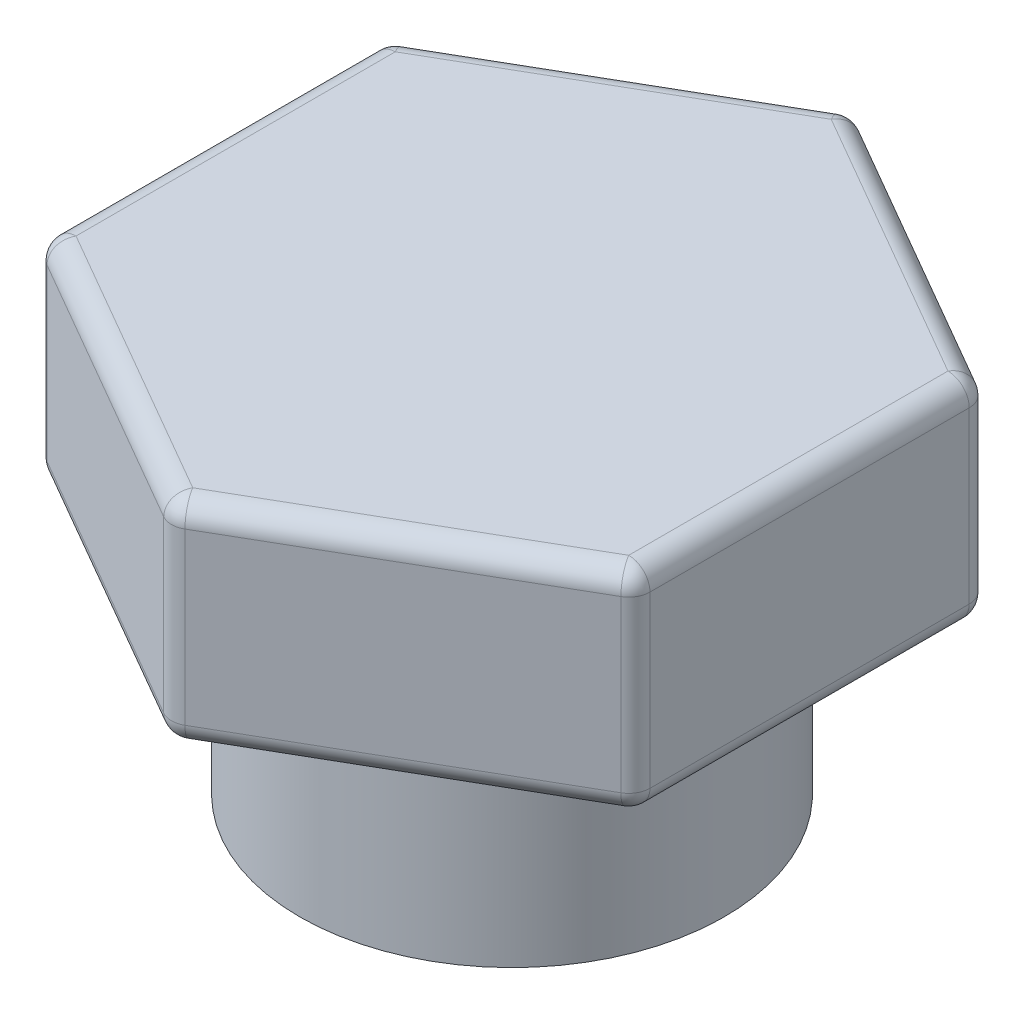
SolidWorks part; units mm, degrees
material "moto_grey"
ref_plane "Front Plane" through (0, 0, 0) normal (0, 0, 1) x (1, 0, 0)
ref_plane "Top Plane" through (0, 0, 0) normal (0, 1, 0) x (1, 0, 0)
ref_plane "Right Plane" through (0, 0, 0) normal (1, 0, 0) x (0, 0, -1)
sketch "Sketch1" plane through (0, 0, 0) normal (0, 1, 0) x (1, 0, 0)
  circle A0 centre (0, 0) radius 5
  dimension "D1" = 10
extrude "Boss-Extrude1" add sketch "Sketch1" along normal blind 5
sketch "Sketch2" plane through (0, 5, 0) normal (0, 1, 0) x (1, 0, 0)
  line L2 (7.0043, -4.0463) -> (7.0064, 4.0428)
  line L3 (7.0064, 4.0428) -> (0.002, 8.0891)
  line L4 (0.002, 8.0891) -> (-7.0043, 4.0463)
  line L5 (-7.0043, 4.0463) -> (-7.0064, -4.0428)
  line L6 (-7.0064, -4.0428) -> (-0.002, -8.0891)
  line L7 (-0.002, -8.0891) -> (7.0043, -4.0463)
  circle A1 centre (0, 0) radius 7.0053 construction
extrude "Boss-Extrude2" add sketch "Sketch2" along normal blind 5
fillet "Fillet1" radius 0.5 18 edges at (7.0053, 10, 0.0018) (7.0053, 5, 0.0018) (3.5011, 10, 6.0677) (7.0043, 7.5, 4.0463) (3.5011, 5, 6.0677) (-3.5042, 10, 6.0659) (-0.002, 7.5, 8.0891) (-3.5042, 5, 6.0659) (-7.0053, 10, -0.0018) (-7.0064, 7.5, 4.0428) (-7.0053, 5, -0.0018) (-3.5011, 10, -6.0677) (-7.0043, 7.5, -4.0463) (-3.5011, 5, -6.0677) (7.0064, 7.5, -4.0428) (3.5042, 10, -6.0659) (0.002, 7.5, -8.0891) (3.5042, 5, -6.0659)
